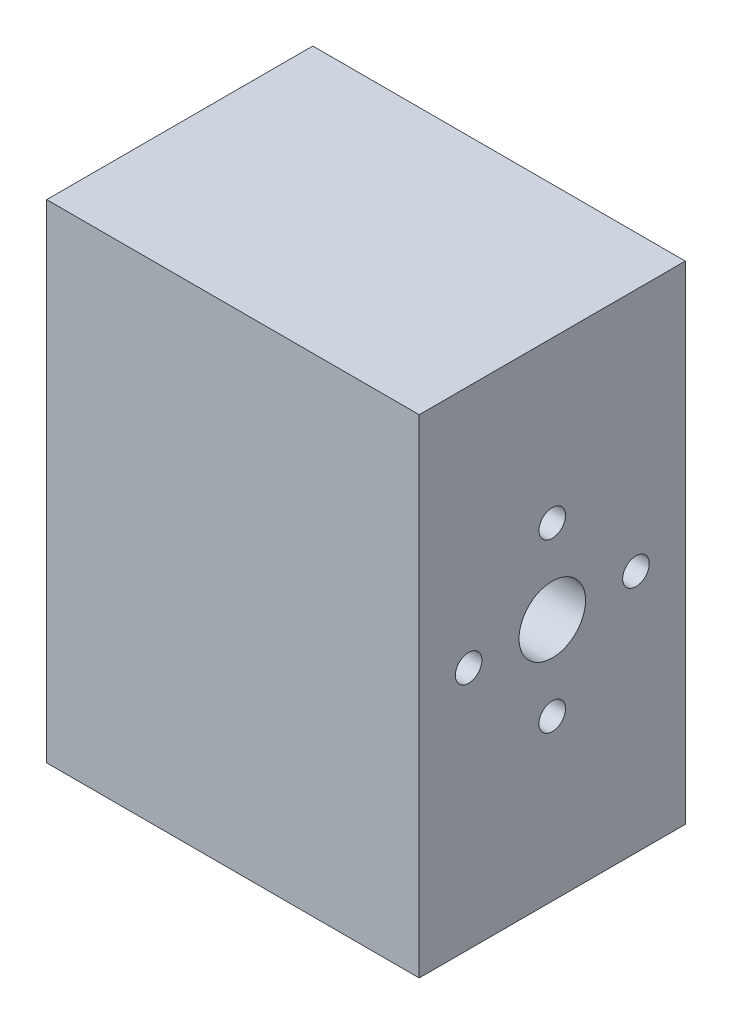
SolidWorks part; units mm, degrees
material "Бальза"
ref_plane "Спереди" through (0, 0, 0) normal (0, 0, 1) x (1, 0, 0)
ref_plane "Сверху" through (0, 0, 0) normal (0, 1, 0) x (1, 0, 0)
ref_plane "Справа" through (0, 0, 0) normal (1, 0, 0) x (0, 0, -1)
sketch "Эскиз1" plane through (0, 0, 0) normal (0, 0, 1) x (1, 0, 0)
  line L1 (0, 0) -> (42, 0)
  line L2 (0, 0) -> (0, 55)
  line L3 (0, 55) -> (42, 55)
  line L4 (42, 0) -> (42, 55)
  dimension "D1" = 42
  dimension "D2" = 55
extrude "Бобышка-Вытянуть1" add sketch "Эскиз1" along normal blind 30
sketch "Эскиз2" plane through (42, 0, 0) normal (1, 0, 0) x (0, 0, -1)
  line L0 (-15, 55) -> (-15, 0) construction
  line L1 (-30, 27.5) -> (0, 27.5) construction
  line L2 (-30, 0) -> (-30, 55) construction
  line L3 (0, 0) -> (0, 55) construction
  line L4 (-30, 0) -> (0, 0) construction
  line L5 (-30, 55) -> (0, 55) construction
  circle A0 centre (-15, 27.5) radius 3.75
  circle A2 centre (-15, 36.9345) radius 1.5
  circle A3 centre (-5.5655, 27.5) radius 1.5
  circle A4 centre (-15, 18.0655) radius 1.5
  circle A5 centre (-24.4345, 27.5) radius 1.5
  dimension "D1" = 7.5
  dimension "D2" = 3
  dimension "D3" = 3
  dimension "D4" = 3
  dimension "D5" = 3
extrude "Вырез-Вытянуть1" cut sketch "Эскиз2" against normal through all
